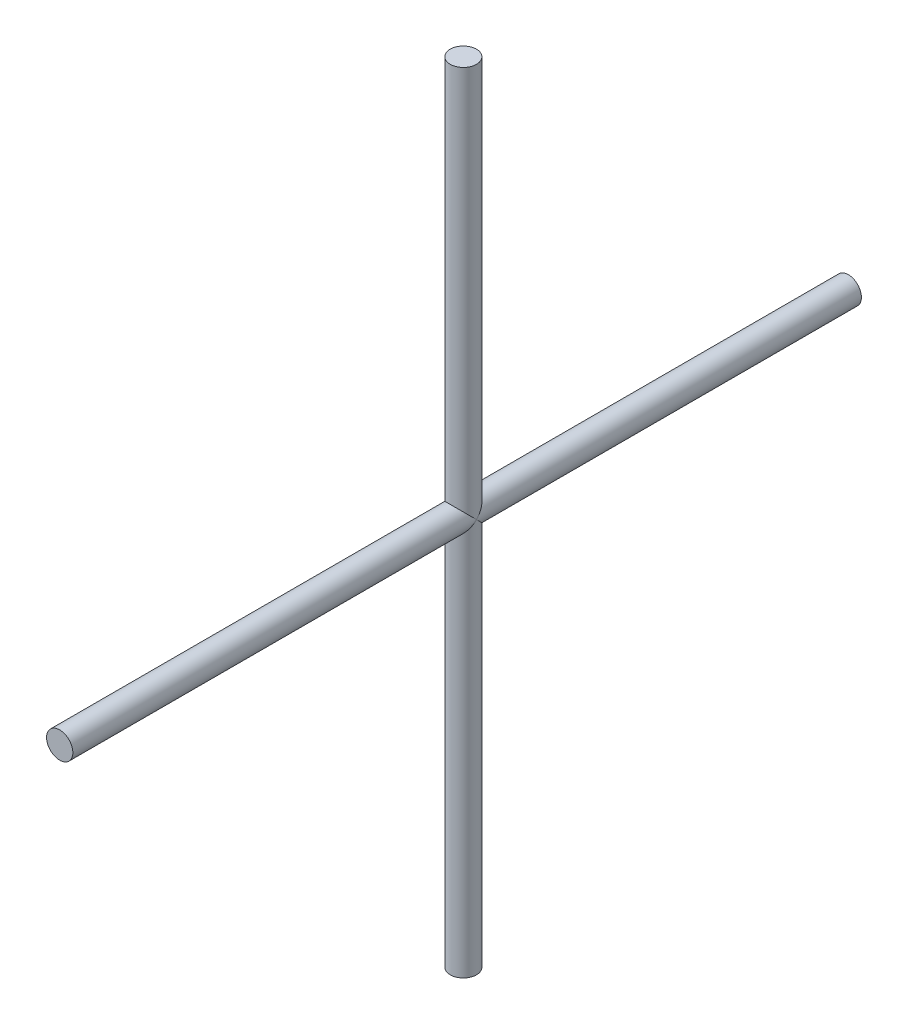
SolidWorks part; units mm, degrees
ref_plane "Front Plane" through (0, 0, 0) normal (0, 0, 1) x (1, 0, 0)
ref_plane "Top Plane" through (0, 0, 0) normal (0, 1, 0) x (1, 0, 0)
ref_plane "Right Plane" through (0, 0, 0) normal (1, 0, 0) x (0, 0, -1)
sketch "Sketch1" plane through (0, 0, 0) normal (0, 0, 1) x (1, 0, 0)
  circle A0 centre (0, 0) radius 5
  dimension "D1" = 10
extrude "Boss-Extrude1" add sketch "Sketch1" along normal blind 300
sketch "Sketch2" plane through (0, 0, 0) normal (0, 1, 0) x (1, 0, 0)
  circle A0 centre (0, -146.4356) radius 5
  dimension "D1" = 10
extrude "Boss-Extrude2" add sketch "Sketch2" along normal mid plane 300
